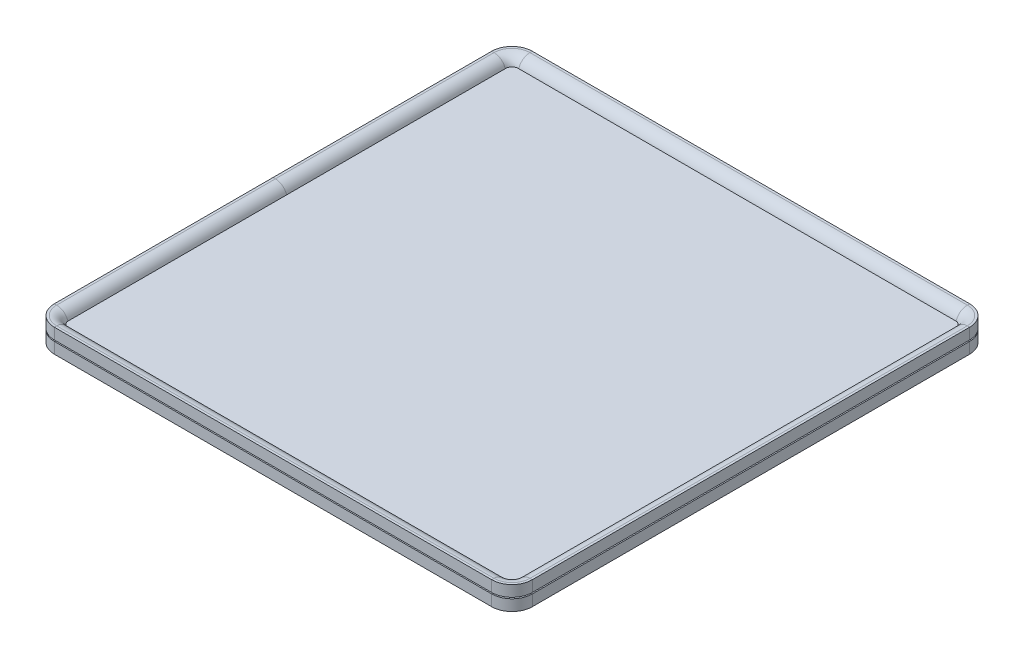
SolidWorks part; units mm, degrees
ref_plane "Front Plane" through (0, 0, 0) normal (0, 0, 1) x (1, 0, 0)
ref_plane "Top Plane" through (0, 0, 0) normal (0, 1, 0) x (1, 0, 0)
ref_plane "Right Plane" through (0, 0, 0) normal (1, 0, 0) x (0, 0, -1)
sketch "Sketch1" plane through (0, 0, 0) normal (0, 1, 0) x (1, 0, 0)
  line L1 (-140, 150) -> (140, 150)
  line L2 (-150, 140) -> (-150, -140)
  line L3 (-140, -150) -> (140, -150)
  line L4 (150, 140) -> (150, -140)
  line L5 (-150, 150) -> (150, -150) construction
  line L6 (-150, -150) -> (150, 150) construction
  arc A0 (-140, -150) -> (-150, -140) centre (-140, -140) cw
  arc A1 (150, -140) -> (140, -150) centre (140, -140) cw
  arc A2 (150, 140) -> (140, 150) centre (140, 140) ccw
  arc A3 (-140, 150) -> (-150, 140) centre (-140, 140) ccw
  point P0 (0, 0)
  dimension "D3" = 10
  dimension "D1" = 300
  dimension "D2" = 300
sketch "Sketch7" plane through (0, 0, 0) normal (0, 0, 1) x (1, 0, 0)
  line L1 (-150, 0.4) -> (-150, -0.4)
  line L2 (-145, 0) -> (-151.1, 0) construction
  line L12 (-150, 0) -> (150, 0) construction
  line L13 (-150, 0) -> (150, 0) construction
  line L15 (-153, 7.5) -> (-151.5, 7.5)
  line L16 (-151.5, -7.5) -> (-153, -7.5)
  line L17 (-153, 7.5) -> (-153, 0.4)
  line L18 (-153, 0.4) -> (-150, 0.4)
  line L19 (-150, -0.4) -> (-153, -0.4)
  line L20 (-153, -0.4) -> (-153, -7.5)
  arc A6 (-151.5, 7.5) -> (-151.5, -7.5) centre (-151.5, 0) cw
  point P5 (-150, 0)
  dimension "D1" = 0.8
  dimension "D2" = 15
  dimension "D4" = 3
  dimension "D3" = 1.5
sweep "Sweep1" add profiles "Sketch7" path "Sketch1"
sketch "Sketch8" plane through (0, 0, 0) normal (0, 1, 0) x (1, 0, 0)
  line L0 (-144, -140) -> (-144, 0) construction
  line L1 (140, -144) -> (-140, -144) construction
  line L2 (144, 140) -> (144, -140) construction
  line L3 (-140, 144) -> (140, 144) construction
  line L4 (-144, 0) -> (-144, 140) construction
  line L5 (-144, -140) -> (-144, 0)
  line L6 (140, -144) -> (-140, -144)
  line L7 (144, 140) -> (144, -140)
  line L8 (-140, 144) -> (140, 144)
  line L9 (-144, 0) -> (-144, 140)
  arc A0 (-144, -140) -> (-140, -144) centre (-140, -140) ccw construction
  arc A1 (140, -144) -> (144, -140) centre (140, -140) ccw construction
  arc A2 (144, 140) -> (140, 144) centre (140, 140) ccw construction
  arc A3 (-140, 144) -> (-144, 140) centre (-140, 140) ccw construction
  arc A4 (-144, -140) -> (-140, -144) centre (-140, -140) ccw
  arc A5 (140, -144) -> (144, -140) centre (140, -140) ccw
  arc A6 (144, 140) -> (140, 144) centre (140, 140) ccw
  arc A7 (-140, 144) -> (-144, 140) centre (-140, 140) ccw
extrude "Boss-Extrude1" add sketch "Sketch8" along normal mid plane 5 separate body
